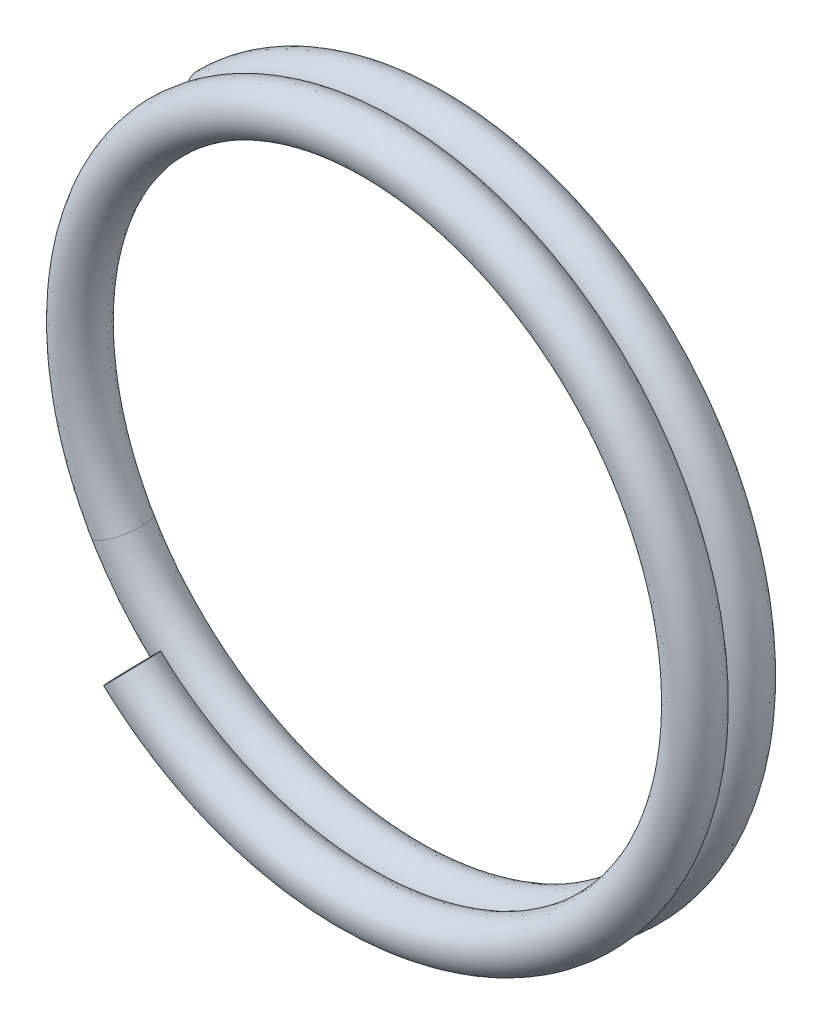
SolidWorks part; units mm, degrees
ref_plane "Спереди" through (0, 0, 0) normal (0, 0, 1) x (1, 0, 0)
ref_plane "Сверху" through (0, 0, 0) normal (0, 1, 0) x (1, 0, 0)
ref_plane "Справа" through (0, 0, 0) normal (1, 0, 0) x (0, 0, -1)
sketch "Эскиз1" plane through (0, 0, 0) normal (0, 0, 1) x (1, 0, 0)
  circle A0 centre (0, 0) radius 13.5
  dimension "D1" = 27
curve "Спираль1" pitch 2 height 3.5 turns 1.75
ref_plane "Плоскость1" through (-9.5459, 9.5459, 0) normal (0.7069, 0.7069, 0.0236) x (0.7073, -0.7065, -0.0236)
sketch "Эскиз2" plane through (-9.5459, 9.5459, 0) normal (0.7069, 0.7069, 0.0236) x (0.7073, -0.7065, -0.0236)
  circle A0 centre (-0.0023, -0.0005) radius 1
  dimension "D1" = 2
sweep "По траектории1" add profiles "Эскиз2" path "Спираль1"
